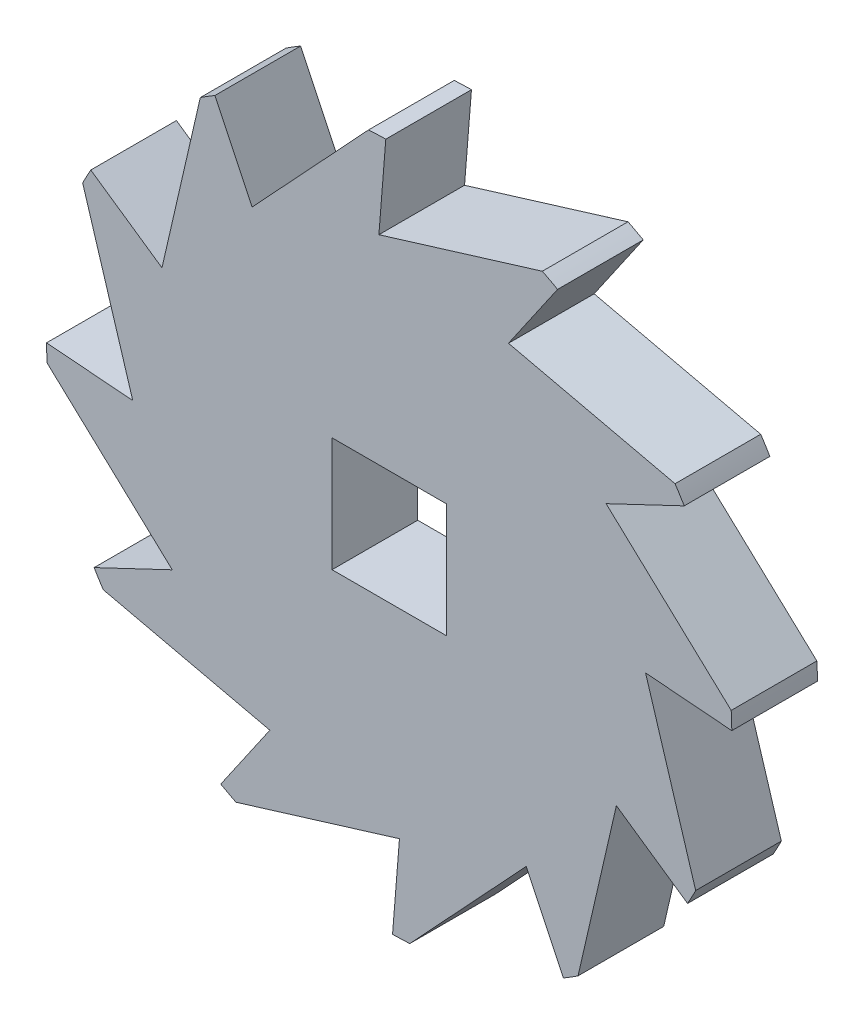
SolidWorks part; units mm, degrees
ref_plane "Piano frontale" through (0, 0, 0) normal (0, 0, 1) x (1, 0, 0)
ref_plane "Piano superiore" through (0, 0, 0) normal (0, 1, 0) x (1, 0, 0)
ref_plane "Piano destro" through (0, 0, 0) normal (1, 0, 0) x (0, 0, -1)
sketch "Schizzo1" plane through (0, 0, 0) normal (0, 0, 1) x (1, 0, 0)
  line L0 (0, 0) -> (0, 42.875) construction
  line L1 (-5, -5) -> (5, -5)
  line L2 (-5, -5) -> (-5, 5)
  line L3 (-5, 5) -> (5, 5)
  line L4 (5, -5) -> (5, 5)
  line L5 (-5, -5) -> (5, 5) construction
  line L6 (-5, 5) -> (5, -5) construction
  line L7 (-0.9, 22.45) -> (13.4094, 26.8363)
  line L8 (-0.9, 22.45) -> (-0.2956, 29.9985)
  line L9 (10.4456, 19.8923) -> (14.7433, 26.1273)
  line L10 (10.4456, 19.8923) -> (25.0311, 16.5362)
  line L11 (18.9923, 12.0044) -> (25.8317, 15.2552)
  line L12 (18.9923, 12.0044) -> (29.9456, 1.8052)
  line L13 (22.45, 0.9) -> (29.9985, 0.2956)
  line L14 (22.45, 0.9) -> (26.8363, -13.4094)
  line L15 (19.8923, -10.4456) -> (26.1273, -14.7433)
  line L16 (19.8923, -10.4456) -> (16.5362, -25.0311)
  line L17 (12.0044, -18.9923) -> (15.2552, -25.8317)
  line L18 (12.0044, -18.9923) -> (1.8052, -29.9456)
  line L19 (0.9, -22.45) -> (0.2956, -29.9985)
  line L20 (0.9, -22.45) -> (-13.4094, -26.8363)
  line L21 (-10.4456, -19.8923) -> (-14.7433, -26.1273)
  line L22 (-10.4456, -19.8923) -> (-25.0311, -16.5362)
  line L23 (-18.9923, -12.0044) -> (-25.8317, -15.2552)
  line L24 (-18.9923, -12.0044) -> (-29.9456, -1.8052)
  line L25 (-22.45, -0.9) -> (-29.9985, -0.2956)
  line L26 (-22.45, -0.9) -> (-26.8363, 13.4094)
  line L27 (-19.8923, 10.4456) -> (-26.1273, 14.7433)
  line L28 (-19.8923, 10.4456) -> (-16.5362, 25.0311)
  line L29 (-12.0044, 18.9923) -> (-15.2552, 25.8317)
  line L30 (-12.0044, 18.9923) -> (-1.8052, 29.9456)
  arc A0 (26.1273, -14.7433) -> (26.8363, -13.4094) centre (0, 0) ccw
  arc A1 (29.9985, 0.2956) -> (29.9456, 1.8052) centre (0, 0) ccw
  arc A2 (25.8317, 15.2552) -> (25.0311, 16.5362) centre (0, 0) ccw
  arc A3 (14.7433, 26.1273) -> (13.4094, 26.8363) centre (0, 0) ccw
  arc A4 (0, 30) -> (-1.8052, 29.9456) centre (0, 0) ccw
  arc A5 (-15.2552, 25.8317) -> (-16.5362, 25.0311) centre (0, 0) ccw
  arc A6 (-29.9985, -0.2956) -> (-29.9456, -1.8052) centre (0, 0) ccw
  arc A7 (-25.8317, -15.2552) -> (-25.0311, -16.5362) centre (0, 0) ccw
  arc A8 (-26.1273, 14.7433) -> (-26.8363, 13.4094) centre (0, 0) ccw
  arc A9 (-14.7433, -26.1273) -> (-13.4094, -26.8363) centre (0, 0) ccw
  arc A10 (0.2956, -29.9985) -> (1.8052, -29.9456) centre (0, 0) ccw
  arc A11 (15.2552, -25.8317) -> (16.5362, -25.0311) centre (0, 0) ccw
  point P0 (0, 0)
  point P11 (0, 0)
  point P13 (0, 0)
  point P14 (0, 0)
  point P15 (0, 0)
  point P19 (0, 0)
  point P23 (0, 0)
  point P27 (0, 0)
  point P31 (0, 0)
  point P35 (0, 0)
  point P39 (0, 0)
  point P43 (0, 0)
  point P47 (0, 0)
  point P51 (0, 0)
  point P55 (0, 0)
  point P59 (0, 0)
  point P60 (0, 0)
  point P61 (0, 0)
  point P62 (0, 0)
  point P63 (0, 0)
  point P64 (0, 0)
  dimension "D6" = 60
  dimension "D1" = 10
  dimension "D2" = 17.45
  dimension "D3" = 4.1
  dimension "D4" = 68.38
  dimension "D5" = 4.578
  dimension "D7" = 12
extrude "Estrusione-Estrusione1" add sketch "Schizzo1" along normal blind 7.5 contours L17 A11 L16 L15 A0 L14 L13 A1 L12 L11 A2 L10 L9 A3 L7 L8 A4 L30 L29 A5 L28 L27 A8 L26 L25 A6 L24 L23 A7 L22 L21 A9 L20 L19 A10 L18 L4 L1 L2 L3
